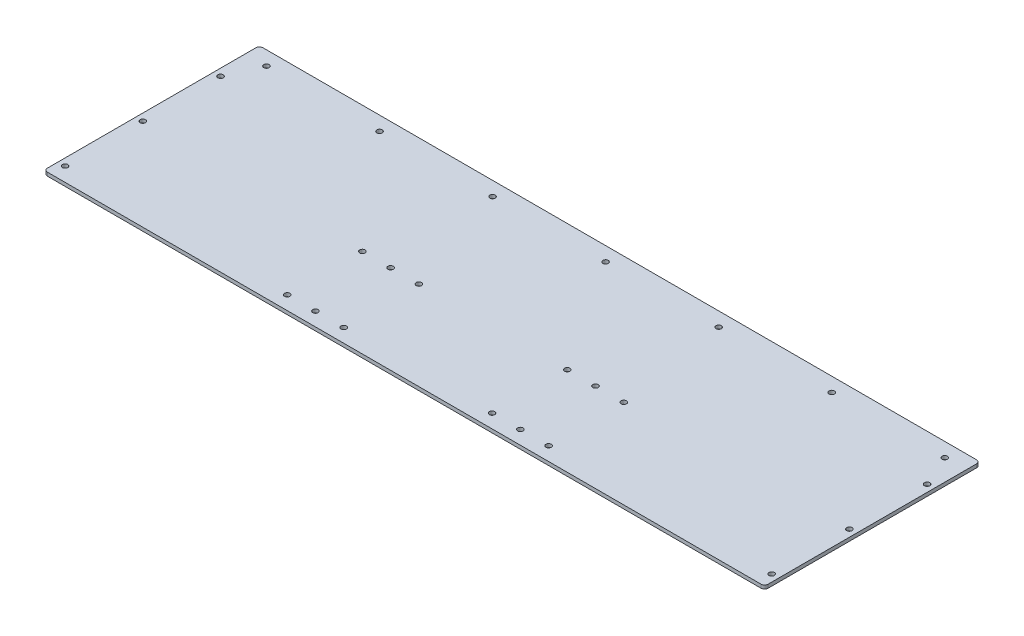
SolidWorks part; units mm, degrees
material "5052-H32"
ref_plane "Front" through (0, 0, 0) normal (0, 0, 1) x (1, 0, 0)
ref_plane "Top" through (0, 0, 0) normal (0, 1, 0) x (1, 0, 0)
ref_plane "Right" through (0, 0, 0) normal (1, 0, 0) x (0, 0, -1)
sketch "Sketch1" plane through (0, 0, 0) normal (0, 1, 0) x (1, 0, 0)
  line L0 (231.775, 0) -> (231.775, 46.0375) construction
  line L1 (0, 0) -> (647.7, 0)
  line L2 (0, 0) -> (0, 193.675)
  line L3 (0, 193.675) -> (647.7, 193.675)
  line L4 (647.7, 0) -> (647.7, 193.675)
  line L5 (231.775, 46.0375) -> (253.2062, 46.0375) construction
  line L6 (206.375, 12.2555) -> (257.175, 12.2555) construction
  line L7 (206.375, 79.8195) -> (257.175, 79.8195) construction
  line L8 (323.85, 193.675) -> (323.85, 180.975) construction
  line L9 (441.325, 79.8195) -> (390.525, 79.8195) construction
  line L10 (441.325, 12.2555) -> (390.525, 12.2555) construction
  line L11 (415.925, 46.0375) -> (394.4937, 46.0375) construction
  line L12 (415.925, 0) -> (415.925, 46.0375) construction
  circle A0 centre (231.775, 46.0375) radius 21.4312 construction
  circle A1 centre (231.775, 12.2555) radius 2.4257
  circle A2 centre (257.175, 12.2555) radius 2.4257
  circle A3 centre (206.375, 12.2555) radius 2.4257
  circle A4 centre (257.175, 79.8195) radius 2.4257
  circle A5 centre (231.775, 79.8195) radius 2.4257
  circle A6 centre (206.375, 79.8195) radius 2.4257
  circle A7 centre (323.85, 180.975) radius 2.4257
  circle A8 centre (425.45, 180.975) radius 2.4257
  circle A9 centre (527.05, 180.975) radius 2.4257
  circle A12 centre (120.65, 180.975) radius 2.4257
  circle A13 centre (222.25, 180.975) radius 2.4257
  circle A14 centre (628.65, 180.975) radius 2.4257
  circle A15 centre (19.05, 180.975) radius 2.4257
  circle A16 centre (415.925, 46.0375) radius 21.4312 construction
  circle A17 centre (441.325, 79.8195) radius 2.4257
  circle A18 centre (415.925, 79.8195) radius 2.4257
  circle A19 centre (390.525, 79.8195) radius 2.4257
  circle A20 centre (441.325, 12.2555) radius 2.4257
  circle A21 centre (390.525, 12.2555) radius 2.4257
  circle A22 centre (415.925, 12.2555) radius 2.4257
  dimension "D3" = 42.8625
  dimension "D5" = 4.8514
  dimension "D9" = 4.8514
  dimension "D1" = 647.7
  dimension "D2" = 193.675
  dimension "D4" = 46.0375
  dimension "D6" = 33.782
  dimension "D7" = 25.4
  dimension "D8" = 12.7
  dimension "D11" = 101.6
  dimension "D12" = 231.775
  dimension "D10" = 4
extrude "Boss-Extrude1" add sketch "Sketch1" along normal blind 3.175
sketch "Sketch2" plane through (0, 3.175, 0) normal (0, 1, 0) x (1, 0, 0)
  line L0 (0, 193.675) -> (0, 0) construction
  line L1 (0, 0) -> (647.7, 0) construction
  line L2 (323.85, 193.675) -> (323.85, -51.395) construction
  line L3 (647.7, 193.675) -> (0, 193.675) construction
  circle A0 centre (6.35, 12.7) radius 2.4257
  circle A1 centre (6.35, 82.55) radius 2.4257
  circle A2 centre (6.35, 152.4) radius 2.4257
  circle A3 centre (6.35, 222.25) radius 2.4257
  circle A4 centre (641.35, 222.25) radius 2.4257
  circle A5 centre (641.35, 152.4) radius 2.4257
  circle A6 centre (641.35, 82.55) radius 2.4257
  circle A7 centre (641.35, 12.7) radius 2.4257
  dimension "D3" = 4.8514
  dimension "D1" = 6.35
  dimension "D2" = 12.7
  dimension "D5" = 69.85
  dimension "D4" = 4
extrude "Cut-Extrude1" cut sketch "Sketch2" against normal through all
fillet "Fillet1" radius 3.175 4 edges at (0, 1.5875, -193.675) (647.7, 1.5875, -193.675) (647.7, 1.5875, 0) (0, 1.5875, 0)
